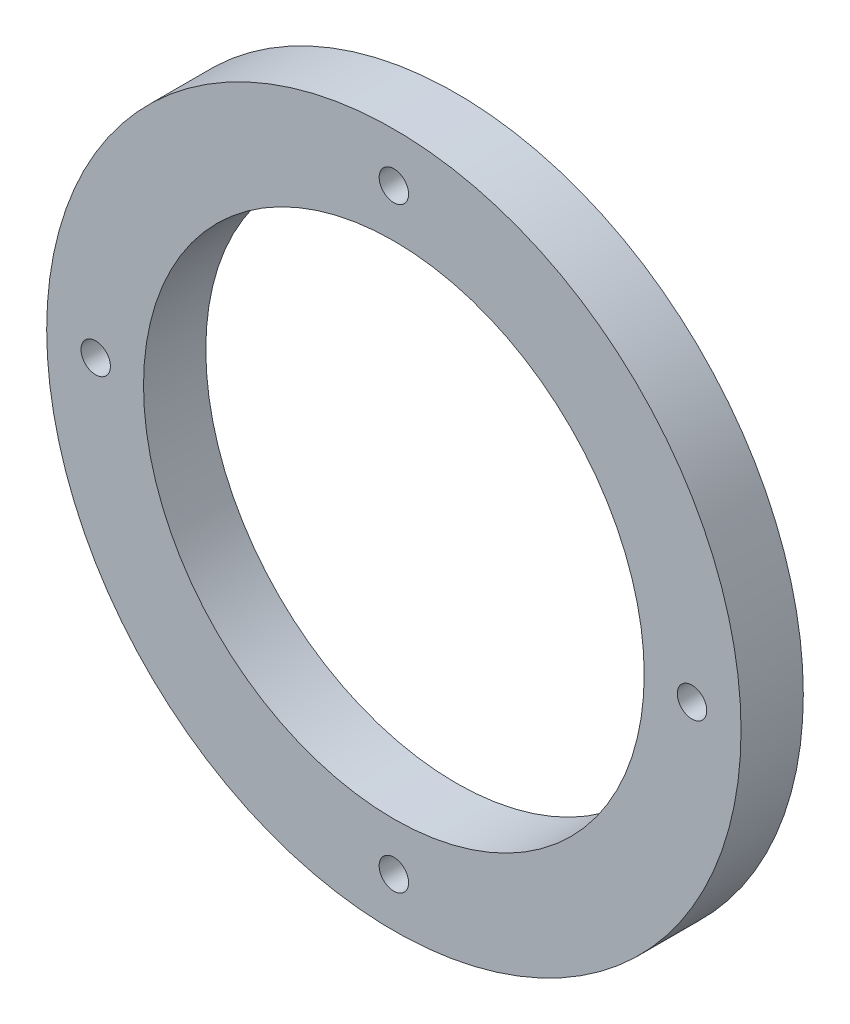
SolidWorks part; units mm, degrees
ref_plane "Front Plane" through (0, 0, 0) normal (0, 0, 1) x (1, 0, 0)
ref_plane "Top Plane" through (0, 0, 0) normal (0, 1, 0) x (1, 0, 0)
ref_plane "Right Plane" through (0, 0, 0) normal (1, 0, 0) x (0, 0, -1)
sketch "Sketch1" plane through (0, 0, 0) normal (0, 0, 1) x (1, 0, 0)
  circle A0 centre (0, 0) radius 35.4
  dimension "D1" = 70.8
extrude "Boss-Extrude1" add sketch "Sketch1" along normal blind 6.35 contours A0
sketch "Sketch2" plane through (0, 0, 6.35) normal (0, 0, 1) x (1, 0, 0)
  circle A0 centre (0, 0) radius 25.527
  dimension "D1" = 51.054
extrude "Cut-Extrude1" cut sketch "Sketch2" against normal blind 6.35
sketch "Sketch3" plane through (0, 0, 6.35) normal (0, 0, 1) x (1, 0, 0)
sketch "Sketch5" plane through (0, 0, 6.35) normal (0, 0, 1) x (1, 0, 0)
  circle A0 centre (0, 0) radius 30.4
  circle A1 centre (0, 30.4) radius 1.5
  circle A2 centre (30.4, 0) radius 1.5
  circle A3 centre (0, -30.4) radius 1.5
  circle A4 centre (-30.4, 0) radius 1.5
  dimension "D1" = 60.8
extrude "Cut-Extrude2" cut sketch "Sketch5" against normal blind 6.35 contours A1 | A2 | A3 | A4
